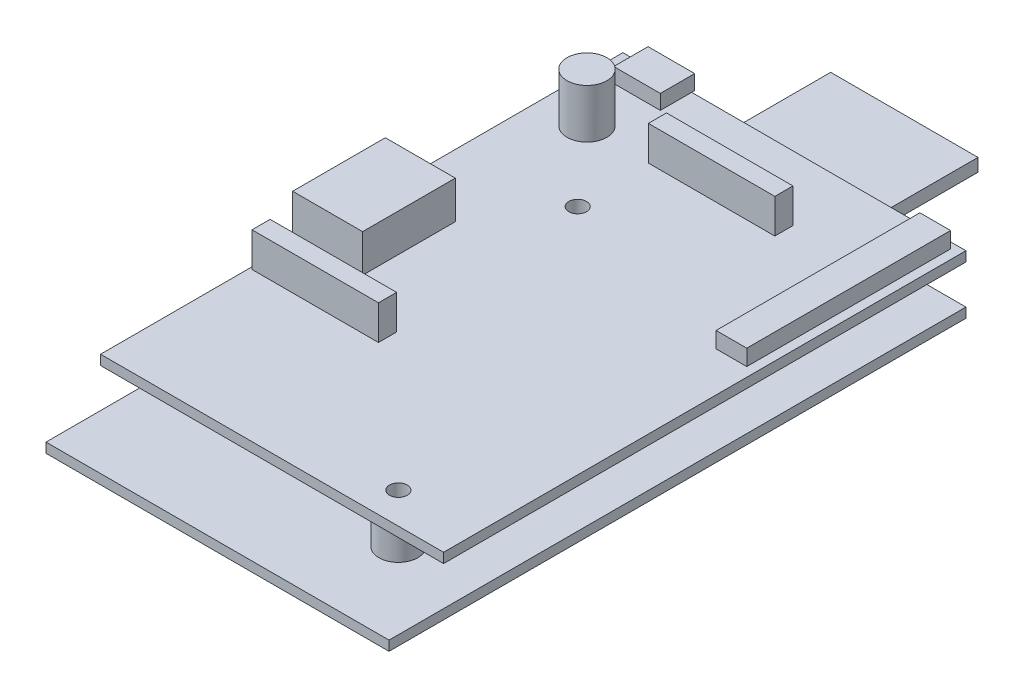
SolidWorks part; units mm, degrees
ref_plane "Front Plane" through (0, 0, 0) normal (0, 0, 1) x (1, 0, 0)
ref_plane "Top Plane" through (0, 0, 0) normal (0, 1, 0) x (1, 0, 0)
ref_plane "Right Plane" through (0, 0, 0) normal (1, 0, 0) x (0, 0, -1)
sketch "Sketch2" plane through (0, 0, 0) normal (0, 1, 0) x (1, 0, 0)
  line L1 (27.94, 42.545) -> (-27.94, 42.545)
  line L2 (27.94, 42.545) -> (27.94, -42.545)
  line L3 (27.94, -42.545) -> (-27.94, -42.545)
  line L4 (-27.94, 42.545) -> (-27.94, -42.545)
  line L5 (27.94, 42.545) -> (-27.94, -42.545) construction
  line L6 (27.94, -42.545) -> (-27.94, 42.545) construction
  point P0 (0, 0)
  dimension "D1" = 55.88
  dimension "D2" = 85.09
extrude "Fiberglass PCB" add sketch "Sketch2" along normal blind 1.6
sketch "Sketch3" plane through (0, 1.6, 0) normal (0, 1, 0) x (1, 0, 0)
  line L0 (-27.94, 42.545) -> (-27.94, -42.545) construction
  line L1 (-24.34, 43.045) -> (-16.74, 43.045)
  line L2 (-24.34, 43.045) -> (-24.34, 37.445)
  line L3 (-24.34, 37.445) -> (-16.74, 37.445)
  line L4 (-16.74, 43.045) -> (-16.74, 37.445)
  line L5 (27.94, 42.545) -> (-27.94, 42.545) construction
  dimension "D1" = 7.6
  dimension "D2" = 5.6
  dimension "D3" = 3.6
  dimension "D4" = 0.5
extrude "USB Micro-B Power" add sketch "Sketch3" along normal blind 2.4
sketch "Sketch4" plane through (0, 1.6, 0) normal (0, 1, 0) x (1, 0, 0)
  line L0 (27.94, -42.545) -> (27.94, 42.545) construction
  line L1 (21.44, 41.545) -> (26.44, 41.545)
  line L2 (21.44, 41.545) -> (21.44, 8.345)
  line L3 (21.44, 8.345) -> (26.44, 8.345)
  line L4 (26.44, 41.545) -> (26.44, 8.345)
  line L5 (27.94, 42.545) -> (-16.74, 42.545) construction
  dimension "D1" = 5
  dimension "D2" = 1.5
  dimension "D3" = 33.2
  dimension "D4" = 1
extrude "Boss-Extrude3" add sketch "Sketch4" along normal blind 2.6
sketch "Sketch5" plane through (0, 1.6, 0) normal (0, 1, 0) x (1, 0, 0)
  line L0 (-27.94, 42.545) -> (-27.94, -42.545) construction
  line L1 (-29.14, 5.045) -> (-17.74, 5.045)
  line L2 (-29.14, 5.045) -> (-29.14, -10.055)
  line L3 (-29.14, -10.055) -> (-17.74, -10.055)
  line L4 (-17.74, 5.045) -> (-17.74, -10.055)
  line L5 (-24.34, 42.545) -> (-27.94, 42.545) construction
  dimension "D1" = 15.1
  dimension "D2" = 11.4
  dimension "D3" = 1.2
  dimension "D4" = 37.5
extrude "Boss-Extrude4" add sketch "Sketch5" along normal blind 6.15
sketch "Sketch6" plane through (0, 1.6, 0) normal (0, 1, 0) x (1, 0, 0)
  line L0 (-27.94, 42.545) -> (-27.94, 5.045) construction
  line L1 (-10.29, 31.995) -> (10.31, 31.995)
  line L2 (-10.29, 31.995) -> (-10.29, 29.045)
  line L3 (-10.29, 29.045) -> (10.31, 29.045)
  line L4 (10.31, 31.995) -> (10.31, 29.045)
  line L5 (27.94, 42.545) -> (-16.74, 42.545) construction
  line L6 (-27.56, -15.305) -> (-6.96, -15.305)
  line L7 (-27.56, -15.305) -> (-27.56, -18.255)
  line L8 (-27.56, -18.255) -> (-6.96, -18.255)
  line L9 (-6.96, -15.305) -> (-6.96, -18.255)
  line L10 (-27.94, -10.055) -> (-17.74, -10.055) construction
  line L11 (27.94, -42.545) -> (27.94, 42.545) construction
  dimension "D1" = 2.95
  dimension "D2" = 20.6
  dimension "D3" = 17.65
  dimension "D4" = 13.5
  dimension "D5" = 20.6
  dimension "D6" = 2.95
  dimension "D7" = 5.25
  dimension "D8" = 34.9
extrude "Boss-Extrude5" add sketch "Sketch6" along normal blind 5.6
sketch "Sketch8" plane through (0, 1.6, 0) normal (0, 1, 0) x (1, 0, 0)
  line L1 (-23.79, 34.459) -> (-23.79, 23.8042) construction
  line L2 (-27.94, 42.545) -> (-27.94, 5.045) construction
  line L3 (-25.2461, 32.545) -> (-15.6058, 32.545) construction
  line L4 (-24.34, 42.545) -> (-27.94, 42.545) construction
  circle A0 centre (-20.54, 29.295) radius 3.25
  dimension "D1" = 6.5
  dimension "D2" = 4.15
  dimension "D3" = 10
extrude "Boss-Extrude6" add sketch "Sketch8" along normal blind 8
sketch "Sketch9" plane through (0, 0, 0) normal (0, -1, 0) x (1, 0, 0)
  line L0 (-27.94, -42.545) -> (-27.94, 42.545) construction
  line L1 (-12.94, -24.545) -> (15.46, -24.545)
  line L2 (-12.94, -24.545) -> (-12.94, -41.345)
  line L3 (-12.94, -41.345) -> (15.46, -41.345)
  line L4 (15.46, -24.545) -> (15.46, -41.345)
  line L5 (27.94, -42.545) -> (-27.94, -42.545) construction
  dimension "D1" = 28.4
  dimension "D2" = 16.8
  dimension "D3" = 43.4
  dimension "D4" = 18
extrude "Boss-Extrude7" add sketch "Sketch9" along normal blind 3.9
sketch "Sketch10" plane through (0, 0, -41.345) normal (0, 0, -1) x (-1, 0, 0)
  line L0 (-15.46, -3.9) -> (-15.46, 0) construction
  line L1 (-13.11, -1.05) -> (10.89, -1.05)
  line L2 (-13.11, -1.05) -> (-13.11, -3.15)
  line L3 (-13.11, -3.15) -> (10.89, -3.15)
  line L4 (10.89, -1.05) -> (10.89, -3.15)
  line L5 (12.94, -3.9) -> (-15.46, -3.9) construction
  dimension "D1" = 2.1
  dimension "D2" = 24
  dimension "D3" = 2.35
  dimension "D4" = 0.75
extrude "Boss-Extrude8" add sketch "Sketch10" along normal blind 18
sketch "Sketch11" plane through (0, 1.6, 0) normal (0, 1, 0) x (1, 0, 0)
  line L0 (13.11, 59.345) -> (-10.89, 59.345) construction
  line L1 (-10.89, 59.345) -> (-10.89, 41.345) construction
  line L4 (-27.94, 42.545) -> (-27.94, 5.045) construction
  line L5 (27.94, 42.545) -> (-16.74, 42.545) construction
  line L6 (-27.94, -42.545) -> (27.94, -42.545) construction
  line L7 (27.94, -42.545) -> (27.94, 42.545) construction
  circle A0 centre (15.494, -37.465) radius 1.45
  circle A1 centre (-9.906, 17.145) radius 1.45
  dimension "D1" = 2.9
  dimension "D2" = 2.9
  dimension "D3" = 18.034
  dimension "D4" = 25.4
  dimension "D5" = 5.08
  dimension "D6" = 12.446
  dimension "D7" = 54.61
  dimension "D8" = 25.4
  dimension "D9" = 42.2
  dimension "D10" = 0.984
extrude "Cut-Extrude1" cut sketch "Sketch11" against normal through all
sketch "Sketch12" plane through (0, 0, 0) normal (0, -1, 0) x (1, 0, 0)
  circle A0 centre (-9.906, -17.145) radius 3.175
  circle A1 centre (15.494, 37.465) radius 3.175
  dimension "D1" = 6.35
  dimension "D2" = 6.35
extrude "Boss-Extrude9" add sketch "Sketch12" along normal blind 6.35
sketch "Sketch13" plane through (0, -6.35, 0) normal (0, -1, 0) x (1, 0, 0)
  line L0 (-27.94, -42.545) -> (-27.94, 42.545) construction
  line L1 (-27.94, -42.545) -> (27.94, -42.545)
  line L2 (-27.94, -42.545) -> (-27.94, 51.435)
  line L3 (-27.94, 51.435) -> (27.94, 51.435)
  line L4 (27.94, -42.545) -> (27.94, 51.435)
  line L5 (27.94, 42.545) -> (27.94, -42.545) construction
  line L7 (27.94, -42.545) -> (-27.94, -42.545) construction
  dimension "D1" = 93.98
extrude "Boss-Extrude10" add sketch "Sketch13" along normal blind 1.5875
sketch "Sketch14" plane through (0, 1.6, 0) normal (0, 1, 0) x (1, 0, 0)
  circle A0 centre (-9.906, 17.145) radius 1.45
  circle A1 centre (15.494, -37.465) radius 1.45
extrude "Cut-Extrude2" cut sketch "Sketch14" against normal through all
